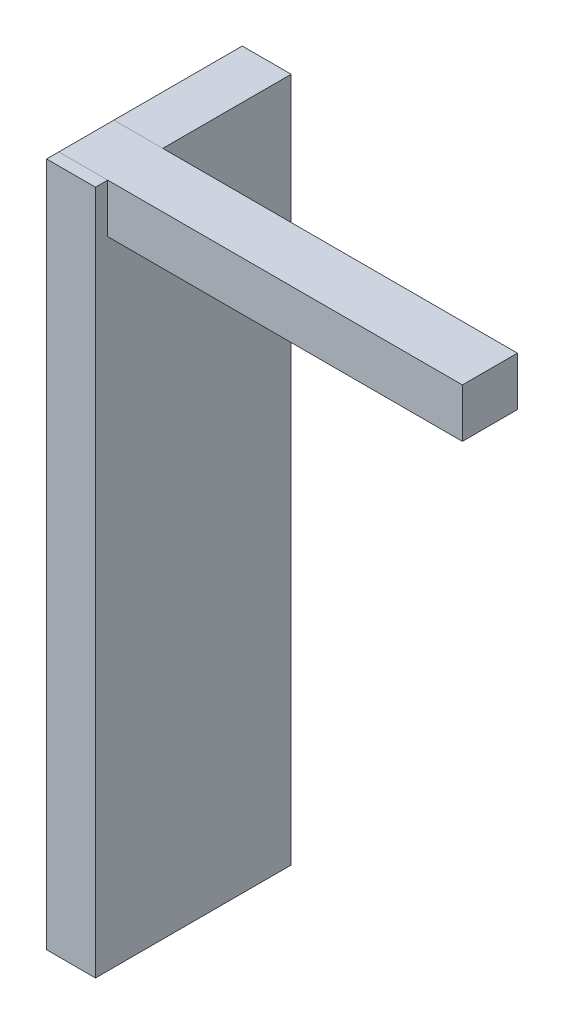
SolidWorks part; units mm, degrees
ref_plane "Front Plane" through (0, 0, 0) normal (0, 0, 1) x (1, 0, 0)
ref_plane "Top Plane" through (0, 0, 0) normal (0, 1, 0) x (1, 0, 0)
ref_plane "Right Plane" through (0, 0, 0) normal (1, 0, 0) x (0, 0, -1)
other "Configuration Table"
sketch "Sketch1" plane through (0, 0, 0) normal (1, 0, 0) x (0, 0, -1)
  line L1 (-24, 192) -> (-40, 192)
  line L2 (-24, 192) -> (-24, 248)
  line L3 (-24, 248) -> (-40, 248)
  line L4 (-40, 192) -> (-40, 248)
  line L5 (-24, 192) -> (-40, 248) construction
  line L6 (-24, 248) -> (-40, 192) construction
  point P0 (-32, 220)
extrude "column" add sketch "Sketch1" along normal blind 4 from offset 46 separate body
sketch "Sketch2" plane through (0, 0, 0) normal (1, 0, 0) x (0, 0, -1)
  line L0 (-24, 248) -> (-40, 248) construction
  line L1 (-34.5, 244) -> (-39, 244)
  line L2 (-34.5, 244) -> (-34.5, 248)
  line L3 (-34.5, 248) -> (-39, 248)
  line L4 (-39, 244) -> (-39, 248)
  line L5 (-34.5, 244) -> (-39, 248) construction
  line L6 (-34.5, 248) -> (-39, 244) construction
  point P0 (-36.75, 246)
extrude "anchor_plate" add sketch "Sketch2" along normal blind 33 from offset 46 separate body
